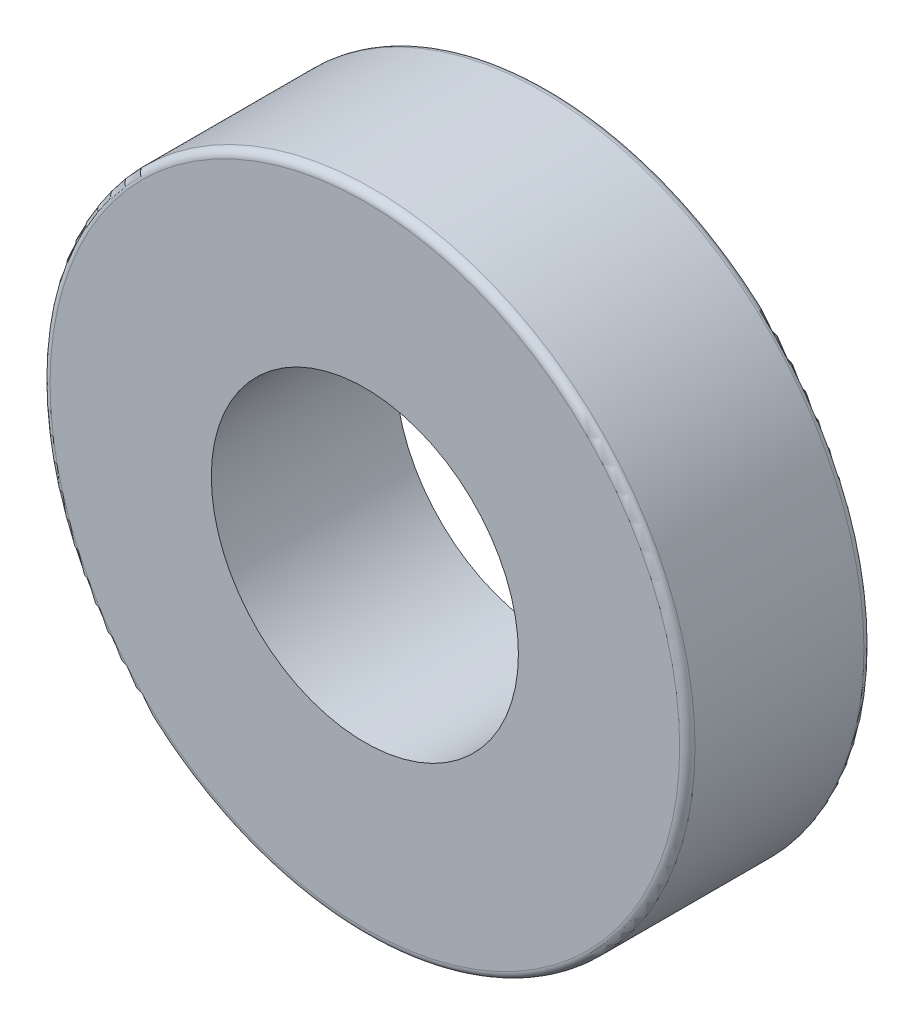
SolidWorks part; units mm, degrees
material "Alloy Steel"
ref_plane "Front Plane" through (0, 0, 0) normal (0, 0, 1) x (1, 0, 0)
ref_plane "Top Plane" through (0, 0, 0) normal (0, 1, 0) x (1, 0, 0)
ref_plane "Right Plane" through (0, 0, 0) normal (1, 0, 0) x (0, 0, -1)
sketch "Sketch2" plane through (0, 0, 0) normal (0, 0, 1) x (1, 0, 0)
  circle A0 centre (0, 0) radius 21
  circle A1 centre (0, 0) radius 10
extrude "Boss-Extrude1" add sketch "Sketch2" along normal blind 12
fillet "Fillet1" radius 0.5 2 edges at (21, 0, 0) (21, 0, 12)
